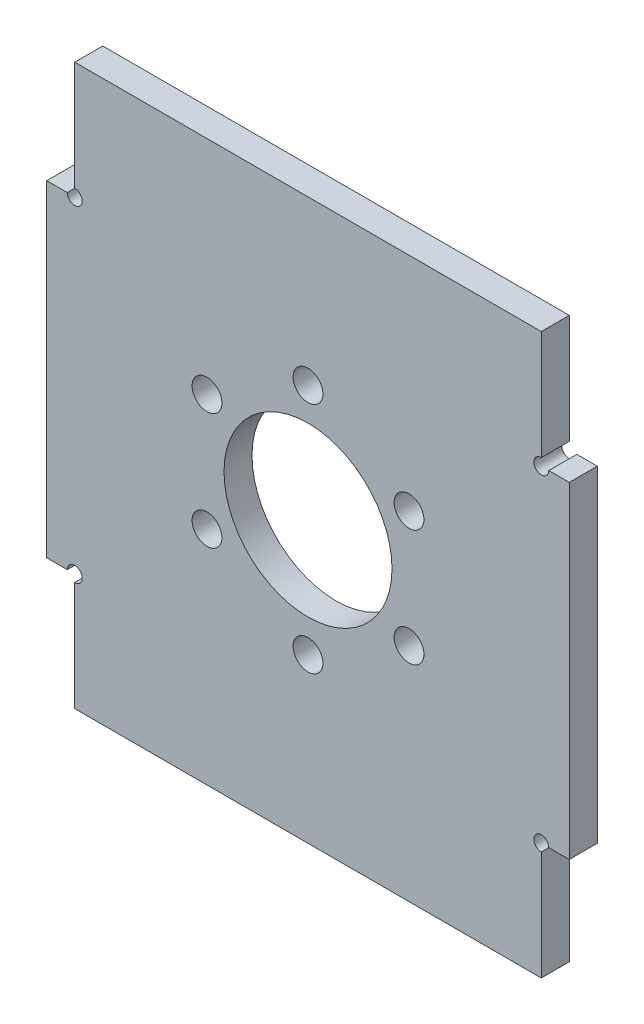
SolidWorks part; units mm, degrees
material "Thornel Mat VMA"
ref_plane "Front Plane" through (0, 0, 0) normal (0, 0, 1) x (1, 0, 0)
ref_plane "Top Plane" through (0, 0, 0) normal (0, 1, 0) x (1, 0, 0)
ref_plane "Right Plane" through (0, 0, 0) normal (1, 0, 0) x (0, 0, -1)
sketch "Sketch1" plane through (0, 0, 0) normal (0, 0, 1) x (1, 0, 0)
  line L0 (0, 0) -> (0, 12.5) construction
  line L1 (-25, -30) -> (25, -30)
  line L2 (-25, -30) -> (-25, 30)
  line L3 (-25, 30) -> (25, 30)
  line L4 (25, -30) -> (25, 30)
  line L5 (-25, -30) -> (25, 30) construction
  line L6 (-25, 30) -> (25, -30) construction
  line L8 (-25, 30) -> (-25, 0)
  line L11 (0, 30) -> (0, 0) construction
  line L12 (0, 0) -> (-25, 0) construction
  circle A0 centre (0, 12.5) radius 1.6
  circle A1 centre (10.8253, 6.25) radius 1.6
  circle A2 centre (10.8253, -6.25) radius 1.6
  circle A3 centre (0, -12.5) radius 1.6
  circle A4 centre (-10.8253, -6.25) radius 1.6
  circle A5 centre (-10.8253, 6.25) radius 1.6
  circle A6 centre (0, 0) radius 9
  point P0 (0, 0)
  point P6 (0, 0)
  point P7 (0, 17.1716)
  point P8 (-25, -0.7233)
  point P24 (0, 0)
  point P26 (0, 31.1488)
  dimension "D5" = 3.2
  dimension "D3" = 12.5
  dimension "D4" = 18
  dimension "D1" = 30
  dimension "D2" = 50
  dimension "D7" = 6
extrude "Boss-Extrude1" add sketch "Sketch1" along normal blind 3
sketch "Sketch2" plane through (0, 0, 3) normal (0, 0, 1) x (1, 0, 0)
  line L0 (-25, -30) -> (-25, 30) construction
  line L1 (-28, -17.5) -> (-22, -17.5)
  line L2 (-28, -17.5) -> (-28, 17.5)
  line L3 (-28, 17.5) -> (-22, 17.5)
  line L4 (-22, -17.5) -> (-22, 17.5)
  line L5 (-28, -17.5) -> (-22, 17.5) construction
  line L6 (-28, 17.5) -> (-22, -17.5) construction
  line L7 (0, 30) -> (0, 0) construction
  line L8 (-25, 30) -> (25, 30) construction
  line L9 (28, 17.5) -> (22, -17.5) construction
  line L10 (28, -17.5) -> (22, 17.5) construction
  line L11 (22, -17.5) -> (22, 17.5)
  line L12 (28, 17.5) -> (22, 17.5)
  line L13 (28, -17.5) -> (28, 17.5)
  line L14 (28, -17.5) -> (22, -17.5)
  point P0 (-25, 0)
  point P16 (25, 0)
  dimension "D1" = 6
  dimension "D2" = 35
extrude "Boss-Extrude2" add sketch "Sketch2" against normal up to surface (3 mm away) up to face at (9, 0, 0)
sketch "Sketch3" plane through (0, 0, 3) normal (0, 0, 1) x (1, 0, 0)
  circle A0 centre (-25, 17.5) radius 0.8
  circle A1 centre (-25, -17.5) radius 0.8
  circle A2 centre (25, 17.5) radius 0.8
  circle A3 centre (25, -17.5) radius 0.8
  dimension "D1" = 1.6
extrude "Cut-Extrude1" cut sketch "Sketch3" against normal through all
